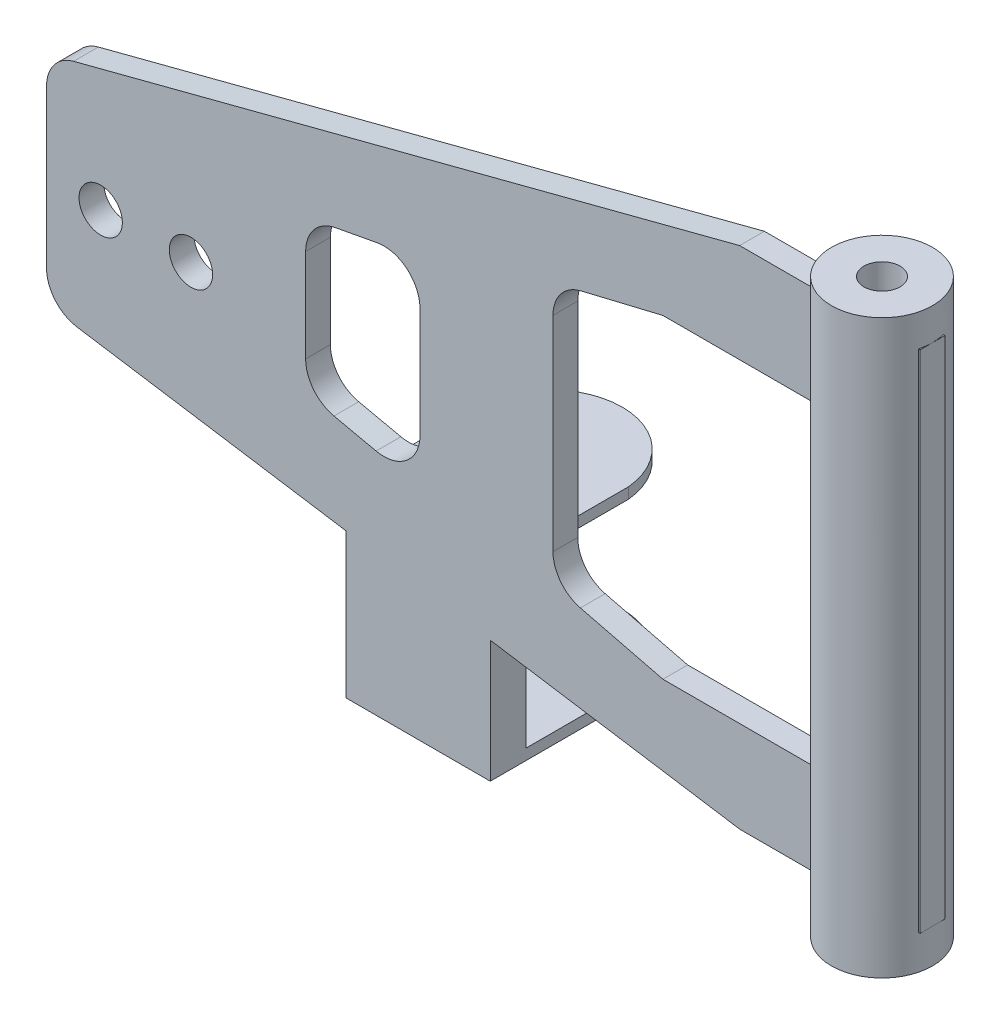
SolidWorks part; units mm, degrees
ref_plane "정면" through (0, 0, 0) normal (0, 0, 1) x (1, 0, 0)
ref_plane "윗면" through (0, 0, 0) normal (0, 1, 0) x (1, 0, 0)
ref_plane "우측면" through (0, 0, 0) normal (1, 0, 0) x (0, 0, -1)
sketch "스케치1" plane through (0, 0, 0) normal (0, 0, 1) x (1, 0, 0)
  line L0 (-140.2923, 27.7405) -> (-140.2923, -32.2595)
  line L6 (51.7077, -62.2595) -> (101.7077, -62.2595)
  line L7 (101.7077, -62.2595) -> (101.7077, 77.7405)
  line L8 (101.7077, 77.7405) -> (51.7077, 77.7405)
  line L9 (51.7077, 77.7405) -> (-140.2923, 27.7405)
  line L10 (-140.2923, -32.2595) -> (51.7077, -62.2595)
  dimension "D1" = 140
  dimension "D2" = 60
  dimension "D3" = 50
  dimension "D4" = 242
  dimension "D5" = 50
  dimension "D6" = 50
extrude "보스-돌출1" add sketch "스케치1" along normal blind 6.86
ref_plane "평면1" through (101.7077, 77.7405, 6.86) normal (-1, 0, 0) x (0, 0, 1)
sketch "스케치3" plane through (0, 77.7405, 0) normal (0, 1, 0) x (1, 0, 0)
  line L0 (101.7077, 6.89) -> (101.7077, -20.61) construction
  line L1 (101.7077, 0) -> (51.7077, 0) construction
  circle A0 centre (87.7077, -3.43) radius 14
  dimension "D1" = 28
  dimension "D2" = 3.43
extrude "보스-돌출2" add sketch "스케치3" against normal blind 140
sketch "스케치4" plane through (0, -62.2595, 0) normal (0, -1, 0) x (1, 0, 0)
  circle A0 centre (87.7077, 3.43) radius 14
extrude "보스-돌출3" add sketch "스케치4" along normal blind 9.54
sketch "스케치5" plane through (0, 77.7405, 0) normal (0, 1, 0) x (1, 0, 0)
  circle A0 centre (87.7077, -3.43) radius 14
extrude "보스-돌출4" add sketch "스케치5" along normal blind 8.87
sketch "스케치6" plane through (0, 0, 0) normal (0, 0, -1) x (-1, 0, 0)
  line L0 (-101.7077, -71.7995) -> (-73.7077, -71.7995) construction
  line L1 (57.3657, -33.7995) -> (17.3657, -33.7995)
  line L2 (57.3657, -33.7995) -> (57.3657, -85.2995)
  line L3 (57.3657, -85.2995) -> (17.3657, -85.2995)
  line L4 (17.3657, -33.7995) -> (17.3657, -85.2995)
  line L5 (-74.1343, 77.7405) -> (-74.1343, -62.2595) construction
  dimension "D1" = 38
  dimension "D2" = 51.5
  dimension "D3" = 40
  dimension "D4" = 91.5
extrude "보스-돌출5" add sketch "스케치6" along normal blind 50
sketch "스케치7" plane through (0, -85.2995, 0) normal (0, -1, 0) x (1, 0, 0)
  line L0 (-57.3657, -50) -> (-57.3657, 0) construction
  line L1 (-17.3657, -50) -> (-17.3657, 0) construction
  line L2 (-57.3657, -31.4105) -> (-57.3657, -50)
  line L3 (-57.3657, -50) -> (-17.3657, -50)
  line L4 (-17.3657, -50) -> (-17.3657, -31.4105)
  arc A0 (-57.3657, -31.4105) -> (-17.3657, -31.4105) centre (-37.3657, -29.588) ccw
extrude "컷-돌출1" cut sketch "스케치7" against normal blind 70
sketch "스케치8" plane through (-17.3657, 0, 0) normal (1, 0, 0) x (0, 0, -1)
  line L0 (31.4105, -33.7995) -> (0, -33.7995) construction
  line L1 (3, -82.2995) -> (61.3799, -82.2995)
  line L2 (3, -82.2995) -> (3, -36.7995)
  line L3 (3, -36.7995) -> (61.3799, -36.7995)
  line L4 (61.3799, -82.2995) -> (61.3799, -36.7995)
  line L5 (31.4105, -85.2995) -> (49.6709, -85.2995) construction
  line L6 (0, -51.4668) -> (0, -85.2995) construction
  dimension "D1" = 3
  dimension "D2" = 3
  dimension "D3" = 3
extrude "컷-돌출2" cut sketch "스케치8" against normal blind 50
sketch "스케치9" plane through (0, -85.2995, 0) normal (0, -1, 0) x (1, 0, 0)
  circle A0 centre (-37.3657, -29.588) radius 5
  dimension "D1" = 10
extrude "컷-돌출3" cut sketch "스케치9" against normal blind 60
sketch "스케치10" plane through (0, 0, 0) normal (0, 0, 1) x (1, 0, 0)
  line L0 (-17.3657, -51.4668) -> (-17.3657, -85.2995)
  line L1 (-17.3657, -85.2995) -> (-57.3657, -85.2995)
  line L2 (-57.3657, -85.2995) -> (-57.3657, -45.2168)
  line L3 (-57.3657, -45.2168) -> (-17.3657, -51.4668)
extrude "보스-돌출6" add sketch "스케치10" along normal blind 6.86
sketch "스케치11" plane through (0, 0, 0) normal (0, 0, -1) x (-1, 0, 0)
  line L0 (140.2923, 27.7405) -> (140.2923, -32.2595) construction
  circle A0 centre (100.2923, -2.2595) radius 6
  circle A1 centre (125.2923, -2.2595) radius 6
  point P6 (0, 0)
  point P7 (140.2923, -2.2595)
  point P8 (-78.1412, -71.7995)
  dimension "D3" = 12
  dimension "D4" = 12
  dimension "D1" = 15
  dimension "D2" = 40
extrude "컷-돌출4" cut sketch "스케치11" against normal blind 6.86
sketch "스케치12" plane through (0, -71.7995, 0) normal (0, -1, 0) x (1, 0, 0)
  circle A0 centre (87.7077, 3.43) radius 5
  dimension "D1" = 10
extrude "컷-돌출5" cut sketch "스케치12" against normal through all both and the other way through all
sketch "스케치13" plane through (0, 0, 0) normal (0, 0, -1) x (-1, 0, 0)
  line L0 (-74.1343, 50.3391) -> (-30.4533, 50.3391)
  line L1 (-74.1343, 77.7405) -> (-74.1343, -62.2595) construction
  line L2 (-30.4533, 50.3391) -> (0, 43.0277)
  line L3 (0, 43.0277) -> (0, -29.3652)
  line L4 (0, -29.3652) -> (-30.4533, -36.9222)
  line L5 (-30.4533, -36.9222) -> (-74.1343, -36.9222)
  line L6 (-74.1343, -36.9222) -> (-74.1343, 50.3391)
  point P7 (0, 39.1142)
  point P10 (-30.285, -36.5934)
  point P11 (0, 43.397)
extrude "컷-돌출6" cut sketch "스케치13" against normal blind 6.86 contours L3 L4 L5 L6 L0 L2
sketch "스케치14" plane through (0, 0, 0) normal (0, 0, -1) x (-1, 0, 0)
  line L0 (68.5246, 24.4983) -> (36.8482, 30.4268)
  line L1 (36.8482, 30.4268) -> (36.8482, -24.5723)
  line L2 (36.8482, -24.5723) -> (68.5246, -17.6085)
  line L3 (68.5246, -17.6085) -> (68.5246, 24.4983)
  point P3 (36.8482, 28.3647)
  point P5 (68.5246, 22.4362)
extrude "컷-돌출7" cut sketch "스케치14" against normal blind 6.86
fillet "필렛1" radius 10 6 edges at (-68.5246, -17.6085, 3.43) (-68.5246, 24.4983, 3.43) (-36.8482, 30.4268, 3.43) (-36.8482, -24.5723, 3.43) (0, 43.0277, 3.43) (0, -29.3652, 3.43)
fillet "필렛2" radius 10 2 edges at (-140.2923, 27.7405, 3.43) (-140.2923, -32.2595, 3.43)
